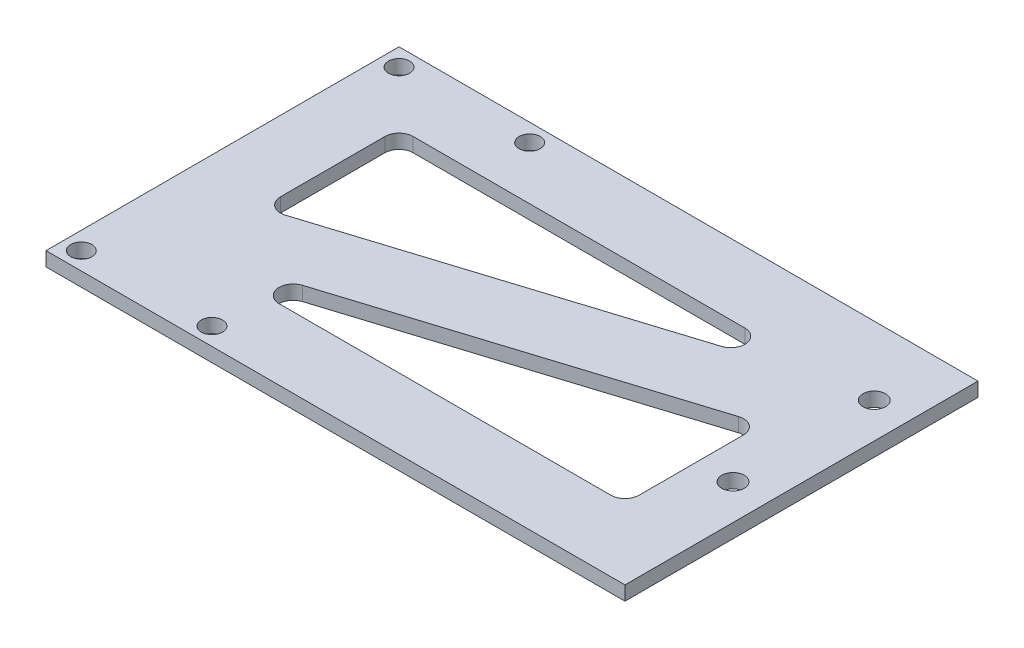
SolidWorks part; units mm, degrees
ref_plane "前视基准面" through (0, 0, 0) normal (0, 0, 1) x (1, 0, 0)
ref_plane "上视基准面" through (0, 0, 0) normal (0, 1, 0) x (1, 0, 0)
ref_plane "右视基准面" through (0, 0, 0) normal (1, 0, 0) x (0, 0, -1)
other "Configuration Table"
sketch "草图1" plane through (0, 0, 0) normal (0, 1, 0) x (1, 0, 0)
  line L0 (2.5, 47.5) -> (2.5, 2.5) construction
  line L1 (0, 0) -> (82, 0)
  line L2 (0, 0) -> (0, 50)
  line L3 (0, 50) -> (82, 50)
  line L4 (82, 0) -> (82, 50)
  line L5 (2.5, 25) -> (0, 25) construction
  line L7 (2.5, 47.5) -> (21, 47.5) construction
  line L8 (21, 47.5) -> (21, 2.5) construction
  line L9 (21, 2.5) -> (2.5, 2.5) construction
  circle A0 centre (2.5, 47.5) radius 1.5
  circle A1 centre (2.5, 2.5) radius 1.5
  circle A2 centre (21, 47.5) radius 1.5
  circle A3 centre (21, 2.5) radius 1.5
  dimension "D3" = 3
  dimension "D1" = 82
  dimension "D2" = 50
  dimension "D4" = 45
  dimension "D5" = 2.5
  dimension "D6" = 18.5
extrude "凸台-拉伸1" add sketch "草图1" along normal blind 2
sketch "草图2" plane through (0, 2, 0) normal (0, 1, 0) x (1, 0, 0)
  line L0 (77, 20.3) -> (77, 40.3) construction
  line L1 (77, 30.3) -> (82, 30.3) construction
  line L2 (82, 0) -> (82, 50) construction
  line L3 (82, 50) -> (0, 50) construction
  circle A0 centre (77, 20.3) radius 1.6
  circle A1 centre (77, 40.3) radius 1.6
  dimension "D2" = 3.2
  dimension "D1" = 20
  dimension "D3" = 5
  dimension "D4" = 19.7
extrude "切除-拉伸1" cut sketch "草图2" against normal blind 2
sketch "草图4" plane through (0, 2, 0) normal (0, 1, 0) x (1, 0, 0)
  line L0 (10, 10) -> (72, 10)
  line L1 (72, 10) -> (72, 29.5163)
  line L2 (72, 29.5163) -> (10, 10)
  line L3 (10, 20.4837) -> (10, 40)
  line L4 (10, 40) -> (72, 40)
  line L5 (72, 40) -> (10, 20.4837)
  line L6 (82, 50) -> (0, 50) construction
  line L7 (0, 0) -> (82, 0) construction
  line L8 (82, 0) -> (82, 50) construction
  line L9 (0, 50) -> (0, 0) construction
  dimension "D1" = 10
  dimension "D2" = 10
  dimension "D3" = 10
  dimension "D4" = 10
  dimension "D5" = 10
extrude "切除-拉伸2" cut sketch "草图4" against normal blind 2
fillet "圆角1" radius 2 6 edges at (10, 1, -40) (72, 1, -40) (10, 1, -20.4837) (72, 1, -29.5163) (72, 1, -10) (10, 1, -10)
